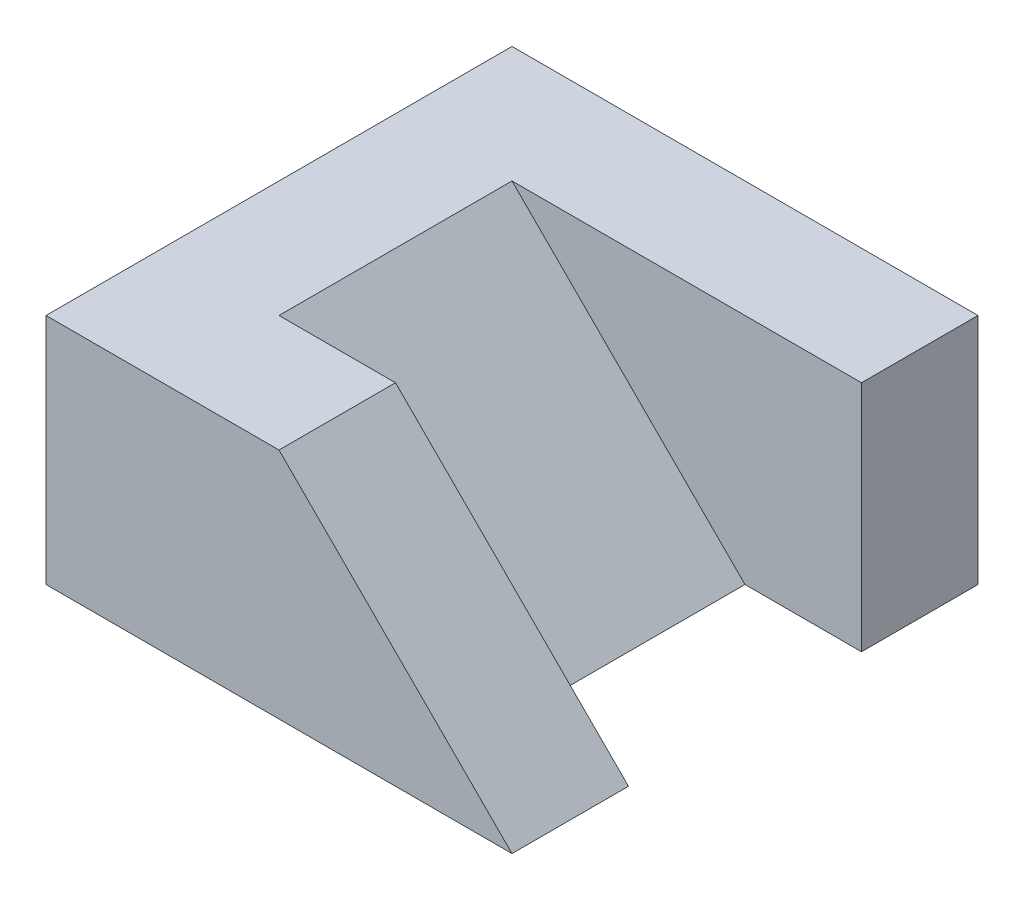
SolidWorks part; units mm, degrees
ref_plane "Front Plane" through (0, 0, 0) normal (0, 0, 1) x (1, 0, 0)
ref_plane "Top Plane" through (0, 0, 0) normal (0, 1, 0) x (1, 0, 0)
ref_plane "Right Plane" through (0, 0, 0) normal (1, 0, 0) x (0, 0, -1)
sketch "Sketch1" plane through (0, 0, 0) normal (0, 1, 0) x (1, 0, 0)
  line L0 (-9.7561, 6.5854) -> (-9.7561, 16.5854)
  line L1 (-9.7561, 16.5854) -> (-49.7561, 16.5854)
  line L2 (-49.7561, 16.5854) -> (-49.7561, -13.4146)
  line L3 (-49.7561, -13.4146) -> (-39.7561, -13.4146)
  line L5 (-19.7561, 6.5854) -> (-9.7561, 6.5854)
  line L6 (-19.7561, 6.5854) -> (-19.7561, -13.4146)
  line L7 (-19.7561, -13.4146) -> (-39.7561, -13.4146)
  dimension "D1" = 10
  dimension "D3" = 20
  dimension "D4" = 40
  dimension "D5" = 10
extrude "Boss-Extrude1" add sketch "Sketch1" along normal blind 20
sketch "Sketch2" plane through (0, 0, 13.4146) normal (0, 0, 1) x (1, 0, 0)
  line L0 (-19.7561, 0) -> (-39.7561, 20)
  line L1 (-49.7561, 20) -> (-19.7561, 20) construction
  line L2 (-49.7561, 20) -> (-49.7561, 0) construction
  line L3 (-19.7561, 0) -> (-19.7561, 20)
  line L4 (-19.7561, 20) -> (-39.7561, 20)
  dimension "D1" = 10
extrude "Cut-Extrude1" cut sketch "Sketch2" against normal blind 20
sketch "Sketch3" plane through (0, 0, 13.4146) normal (0, 0, 1) x (1, 0, 0)
  line L0 (-49.7561, 20) -> (-49.7561, 0)
  line L1 (-49.7561, 0) -> (-9.7561, 0)
  line L3 (-9.7561, 0) -> (-29.7561, 20)
  line L5 (-39.7561, 20) -> (-9.7561, 20) construction
  line L6 (-29.7561, 20) -> (-49.7561, 20)
  dimension "D1" = 45
extrude "Boss-Extrude2" add sketch "Sketch3" along normal blind 10 contours L3 L6 L0 L1
